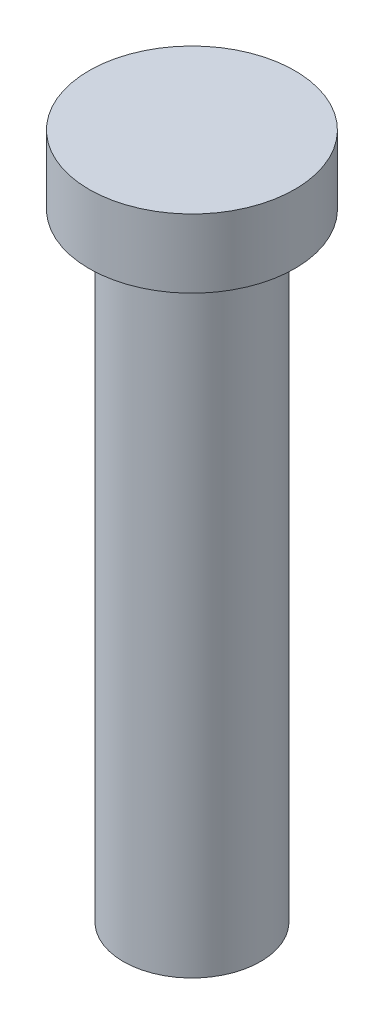
SolidWorks part; units mm, degrees
ref_plane "Front Plane" through (0, 0, 0) normal (0, 0, 1) x (1, 0, 0)
ref_plane "Top Plane" through (0, 0, 0) normal (0, 1, 0) x (1, 0, 0)
ref_plane "Right Plane" through (0, 0, 0) normal (1, 0, 0) x (0, 0, -1)
sketch "Sketch1" plane through (0, 0, 0) normal (0, 1, 0) x (1, 0, 0)
  circle A0 centre (0, 0) radius 1
  dimension "D1" = 2
extrude "Boss-Extrude1" add sketch "Sketch1" along normal blind 9
sketch "Sketch2" plane through (0, 9, 0) normal (0, 1, 0) x (1, 0, 0)
  circle A0 centre (0, 0) radius 1.5
  dimension "D1" = 3
extrude "Boss-Extrude2" add sketch "Sketch2" along normal blind 1
